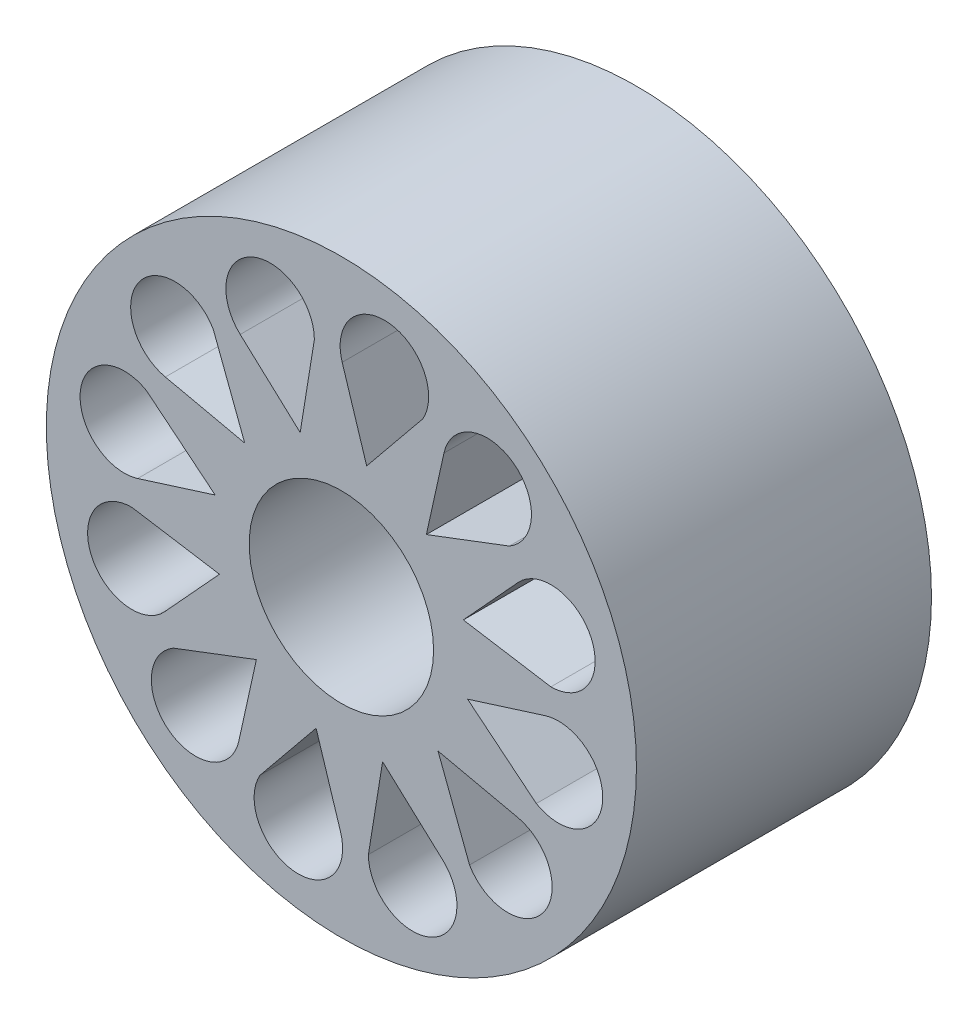
SolidWorks part; units mm, degrees
material "PE High Density"
ref_plane "Front Plane" through (0, 0, 0) normal (0, 0, 1) x (1, 0, 0)
ref_plane "Top Plane" through (0, 0, 0) normal (0, 1, 0) x (1, 0, 0)
ref_plane "Right Plane" through (0, 0, 0) normal (1, 0, 0) x (0, 0, -1)
sketch "Sketch1" plane through (0, 0, 0) normal (0, 0, 1) x (1, 0, 0)
  circle A0 centre (0, 0) radius 12.7
  circle A1 centre (0, 0) radius 3.9688
  dimension "D1" = 25.4
  dimension "D2" = 7.9375
extrude "Boss-Extrude1" add sketch "Sketch1" along normal blind 12.7
sketch "Sketch2" plane through (0, 0, 12.7) normal (0, 0, 1) x (1, 0, 0)
  line L0 (-1.7732, 5.2481) -> (-1.1631, 9.0173)
  line L1 (-1.7732, 5.2481) -> (-4.3548, 7.6125)
  arc A0 (-1.2604, 8.4164) -> (-4.3548, 7.6125) centre (-3.0681, 9.0173) ccw
extrude "Cut-Extrude1" cut sketch "Sketch2" against normal through all contours L0 A0 L1
pattern_circular "CirPattern1" count 12 over 360 about axis through (0, 0, 0) along (0, 0, 1) of "Cut-Extrude1"
